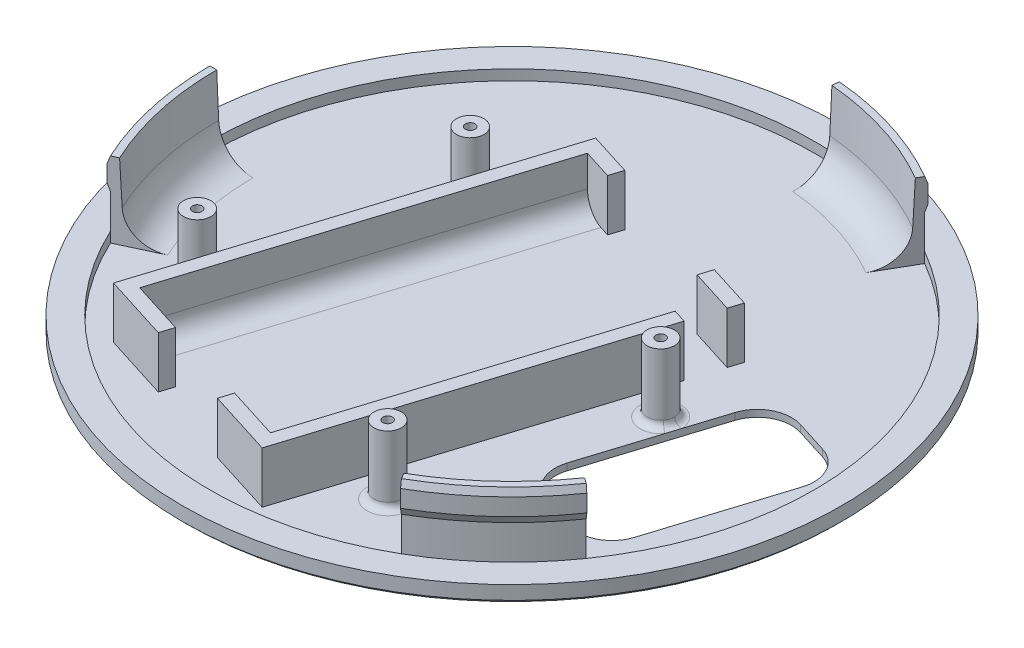
SolidWorks part; units mm, degrees
ref_plane "Front Plane" through (0, 0, 0) normal (0, 0, 1) x (1, 0, 0)
ref_plane "Top Plane" through (0, 0, 0) normal (0, 1, 0) x (1, 0, 0)
ref_plane "Right Plane" through (0, 0, 0) normal (1, 0, 0) x (0, 0, -1)
sketch "Sketch1" plane through (0, 0, 0) normal (0, 1, 0) x (1, 0, 0)
  circle A0 centre (0, 0) radius 96.15
  dimension "D1" = 192.3
extrude "Boss-Extrude1" add sketch "Sketch1" along normal blind 5
sketch "Sketch2" plane through (0, 5, 0) normal (0, 1, 0) x (1, 0, 0)
  circle A0 centre (0, 0) radius 88.15
  circle A1 centre (0, 0) radius 96.15 construction
  dimension "D1" = 8
extrude "Cut-Extrude1" cut sketch "Sketch2" against normal blind 3
sketch "Sketch3" plane through (0, 0, 0) normal (0, 0, 1) x (1, 0, 0)
  line L1 (-88.15, 2) -> (-88.15, 15)
  line L2 (-88.15, 15) -> (-88.8779, 17)
  line L3 (-88.8779, 17) -> (-88.8779, 22)
  line L4 (-88.8779, 22) -> (-88.15, 24)
  line L5 (-88.15, 24) -> (-86.15, 24)
  line L6 (-86.15, 24) -> (-85.15, 2)
  line L7 (-85.15, 2) -> (-88.15, 2)
  line L8 (96.15, 5) -> (88.15, 5)
  line L9 (-88.15, 5) -> (-96.15, 5)
  line L10 (-88.15, 5) -> (-96.15, 5) construction
  point P12 (-84.1971, 2)
  point P13 (-85.15, 24)
  point P14 (-87.2221, 24)
  dimension "D1" = 10
  dimension "D2" = 20
  dimension "D3" = 2
  dimension "D4" = 5
  dimension "D5" = 3
  dimension "D6" = 2
ref_axis "Axis1" through (0, 2, 0) along (0, 1, 0)
revolve "Revolve1" add sketch "Sketch3" angle 25 about axis through (0, 2, 0) along (0, 1, 0)
pattern_circular "CirPattern1" count 3 over 360 about axis through (0, 0, 0) along (0, 1, 0) of "Revolve1"
fillet "Fillet1" radius 10 3 edges at (25.6051, 2, -81.209) (57.5265, 2, 62.7792) (-83.1316, 2, 18.4298)
sketch "Sketch4" plane through (0, 2, 0) normal (0, 1, 0) x (1, 0, 0)
  line L0 (-55.9331, -35.9135) -> (25.2186, -61.5005) construction
  line L5 (-55.9331, -35.9135) -> (-36.8383, 24.6475) construction
  line L6 (25.2186, -61.5005) -> (44.3134, -0.9395) construction
  line L7 (-36.8383, 24.6475) -> (44.3134, -0.9395) construction
  line L8 (-68.5116, -31.9475) -> (37.7971, -65.4665) construction
  line L9 (3.7376, 11.854) -> (22.7316, 72.0955) construction
  arc A0 (37.7971, 65.4665) -> (6.5885, 75.3066) centre (0, 0) ccw construction
  circle A1 centre (-36.8383, 24.6475) radius 4
  circle A2 centre (44.3134, -0.9395) radius 4
  circle A3 centre (25.2186, -61.5005) radius 4
  circle A4 centre (-55.9331, -35.9135) radius 4
  circle A5 centre (-36.8383, 24.6475) radius 1.4
  circle A6 centre (44.3134, -0.9395) radius 1.4
  circle A7 centre (25.2186, -61.5005) radius 1.4
  circle A8 centre (-55.9331, -35.9135) radius 1.4
  dimension "D3" = 8
  dimension "D4" = 2.8
  dimension "D1" = 63.5
  dimension "D2" = 85.09
extrude "Boss-Extrude2" add sketch "Sketch4" along normal blind 20
chamfer "Chamfer1" distance 1 angle 45 1 edges at (0, 0, 96.15)
sketch "Sketch5" plane through (0, 2, 0) normal (0, 1, 0) x (1, 0, 0)
  line L0 (-55.9331, -35.9135) -> (25.2186, -61.5005) construction
  line L1 (-55.9331, -35.9135) -> (-36.8383, 24.6475) construction
  line L2 (25.2186, -61.5005) -> (44.3134, -0.9395) construction
  line L3 (-36.8383, 24.6475) -> (44.3134, -0.9395) construction
  line L4 (-15.3573, -48.707) -> (3.7376, 11.854) construction
  line L5 (6.3905, -76.8702) -> (-49.3257, -59.3029)
  line L6 (6.3905, -76.8702) -> (37.706, 22.4499)
  line L7 (-49.3257, -59.3029) -> (-18.0102, 40.0172)
  line L8 (37.706, 22.4499) -> (-18.0102, 40.0172)
  line L9 (6.3905, -76.8702) -> (-18.0102, 40.0172) construction
  line L10 (-49.3257, -59.3029) -> (37.706, 22.4499) construction
  line L11 (9.0025, -81.8878) -> (42.7237, 25.062)
  line L12 (42.7237, 25.062) -> (-20.6222, 45.0349)
  line L13 (-54.3434, -61.915) -> (-20.6222, 45.0349)
  line L14 (9.0025, -81.8878) -> (-54.3434, -61.915)
  point P9 (-5.8099, -18.4265)
  point P10 (-5.8099, -18.4265)
  dimension "D1" = 104.14
  dimension "D2" = 58.42
  dimension "D3" = 4
extrude "Boss-Extrude3" add sketch "Sketch5" along normal blind 15
sketch "Sketch6" plane through (0, 17, 0) normal (0, 1, 0) x (1, 0, 0)
  line L0 (28.722, 25.2826) -> (29.9248, 29.0974)
  line L1 (28.722, 25.2826) -> (-9.4267, 37.3108)
  line L2 (29.9248, 29.0974) -> (-8.2239, 41.1257)
  line L3 (-9.4267, 37.3108) -> (-8.2239, 41.1257)
  line L4 (37.706, 22.4499) -> (-18.0102, 40.0172) construction
  line L5 (42.7237, 25.062) -> (-20.6222, 45.0349) construction
  line L6 (-18.0102, 40.0172) -> (-49.3257, -59.3029) construction
  line L7 (34.6989, 12.9128) -> (37.706, 22.4499)
  line L8 (34.6989, 12.9128) -> (38.5138, 11.7099)
  line L9 (37.706, 22.4499) -> (41.5208, 21.2471)
  line L10 (38.5138, 11.7099) -> (41.5208, 21.2471)
  line L11 (6.3905, -76.8702) -> (37.706, 22.4499) construction
  line L13 (9.0025, -81.8878) -> (42.7237, 25.062) construction
  point P17 (41.5208, 21.2471)
  dimension "D1" = 40
  dimension "D2" = 9
  dimension "D3" = 10
extrude "Cut-Extrude2" cut sketch "Sketch6" against normal up to surface (15 mm away) up to face at (-5.8099, 2, 18.4265)
sketch "Sketch7" plane through (0, 2, 0) normal (0, 1, 0) x (1, 0, 0)
  line L0 (39.2878, -35.7179) -> (57.0294, 20.5514)
  line L1 (39.2878, -35.7179) -> (67.8993, -44.7391)
  line L2 (57.0294, 20.5514) -> (85.6409, 11.5302)
  line L3 (67.8993, -44.7391) -> (85.6409, 11.5302)
  line L4 (9.0025, -81.8878) -> (38.5138, 11.7099) construction
  line L5 (34.6989, 12.9128) -> (38.5138, 11.7099) construction
  line L6 (42.7237, 25.062) -> (29.9248, 29.0974) construction
  point P10 (84.189, 11.988)
  dimension "D1" = 15
  dimension "D2" = 45
  dimension "D3" = 30
extrude "Cut-Extrude3" cut sketch "Sketch7" against normal through all
fillet "Fillet2" radius 10 4 edges at (85.6409, 1, -11.5302) (57.0294, 1, -20.5514) (39.2878, 1, 35.7179) (67.8993, 1, 44.7391)
fillet "Fillet3" radius 2 4 edges at (-36.8383, 2, -20.6475) (-55.9331, 2, 39.9135) (44.3134, 2, 4.9395) (25.2186, 2, 65.5005)
fillet "Fillet4" radius 6 2 edges at (-33.6679, 2, 9.6429) (20.5447, 2, 31.9787)
sketch "Sketch8" plane through (0, 17, 0) normal (0, 1, 0) x (1, 0, 0)
  line L0 (-10.0718, -75.8737) -> (-35.269, -67.9291)
  line L1 (-10.0718, -75.8737) -> (-8.869, -72.0589)
  line L2 (-35.269, -67.9291) -> (-34.0662, -64.1142)
  line L3 (-8.869, -72.0589) -> (-34.0662, -64.1142)
  line L4 (-54.3434, -61.915) -> (9.0025, -81.8878) construction
  line L5 (-49.3257, -59.3029) -> (6.3905, -76.8702) construction
  line L6 (9.0025, -81.8878) -> (38.5138, 11.7099) construction
  line L7 (-20.6222, 45.0349) -> (-54.3434, -61.915) construction
  point P6 (-31.4632, -64.9349)
  dimension "D1" = 20
  dimension "D2" = 20
extrude "Cut-Extrude4" cut sketch "Sketch8" against normal up to surface (15 mm away) up to face at (-36.8383, 2, -18.6475)
